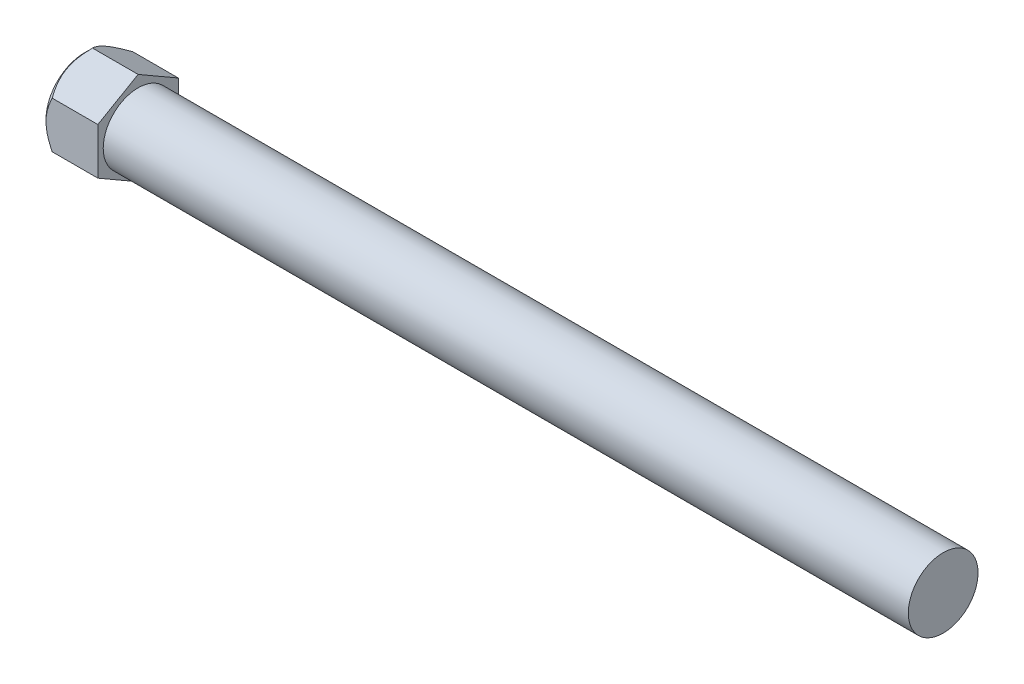
SolidWorks part; units mm, degrees
ref_plane "Front Plane" through (0, 0, 0) normal (0, 0, 1) x (1, 0, 0)
ref_plane "Top Plane" through (0, 0, 0) normal (0, 1, 0) x (1, 0, 0)
ref_plane "Right Plane" through (0, 0, 0) normal (1, 0, 0) x (0, 0, -1)
sketch "Sketch2" plane through (0, 0, 0) normal (1, 0, 0) x (0, 0, -1)
  line L1 (0, -4.3994) -> (3.81, -2.1997)
  line L2 (3.81, -2.1997) -> (3.81, 2.1997)
  line L3 (3.81, 2.1997) -> (0, 4.3994)
  line L4 (0, 4.3994) -> (-3.81, 2.1997)
  line L5 (-3.81, 2.1997) -> (-3.81, -2.1997)
  line L6 (-3.81, -2.1997) -> (0, -4.3994)
  circle A0 centre (0, 0) radius 3.81 construction
  dimension "D1" = 7.62
extrude "Boss-Extrude1" add sketch "Sketch2" along normal blind 5.08
sketch "Sketch3" plane through (5.08, 0, 0) normal (1, 0, 0) x (0, 0, -1)
  circle A0 centre (0, 0) radius 3.302
  dimension "D1" = 6.604
extrude "Boss-Extrude2" add sketch "Sketch3" along normal blind 76.2
sketch "Sketch4" plane through (0, 0, 0) normal (0, 0, 1) x (1, 0, 0)
  line L0 (5.08, 4.3994) -> (0, 4.3994) construction
  line L1 (0, 4.3994) -> (0, 2.1997) construction
  line L2 (5.08, 4.3994) -> (0.762, 4.3994)
  line L3 (0, 3.6374) -> (0, 2.1997)
  line L4 (0.762, 4.3994) -> (0, 3.6374)
  line L5 (0, 2.1997) -> (-1.1468, 2.1997)
  line L6 (-1.1468, 2.1997) -> (-1.1468, 5.5809)
  line L7 (-1.1468, 5.5809) -> (5.08, 5.5809)
  line L8 (5.08, 5.5809) -> (5.08, 4.3994)
  line L9 (0, 0) -> (6.8323, 0) construction
  line L10 (0, 2.1997) -> (0, -2.1997) construction
revolve "Cut-Revolve1" cut sketch "Sketch4" angle 360 about L9
